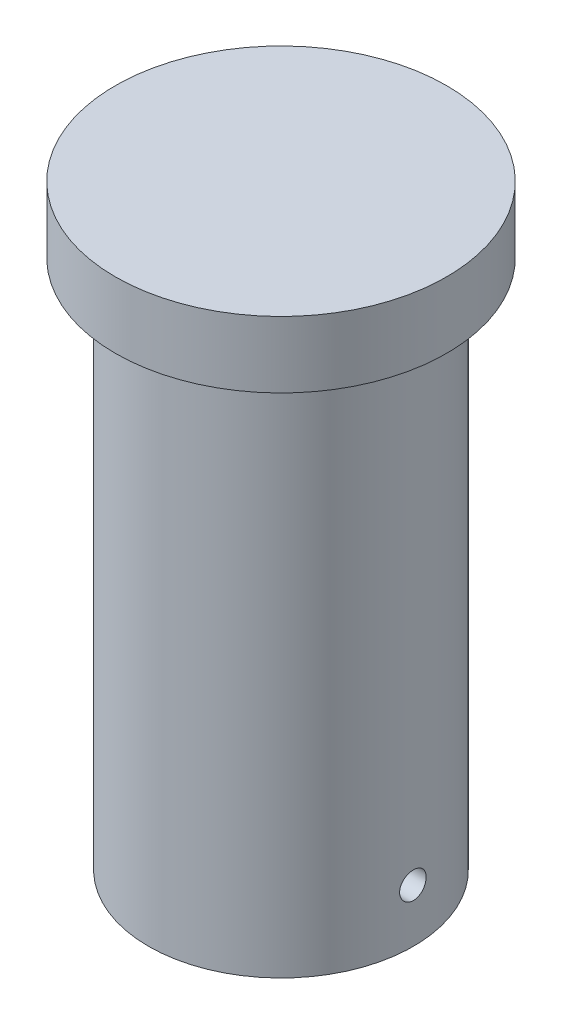
SolidWorks part; units mm, degrees
ref_plane "Front Plane" through (0, 0, 0) normal (0, 0, 1) x (1, 0, 0)
ref_plane "Top Plane" through (0, 0, 0) normal (0, 1, 0) x (1, 0, 0)
ref_plane "Right Plane" through (0, 0, 0) normal (1, 0, 0) x (0, 0, -1)
sketch "Sketch1" plane through (0, 0, 0) normal (0, 1, 0) x (1, 0, 0)
  circle A0 centre (0, 0) radius 5
  dimension "D1" = 10
extrude "Boss-Extrude1" add sketch "Sketch1" along normal blind 20
sketch "Sketch3" plane through (0, 20, 0) normal (0, 1, 0) x (1, 0, 0)
  circle A0 centre (0, 0) radius 6.25
  dimension "D1" = 12.5
extrude "Boss-Extrude3" add sketch "Sketch3" along normal blind 2.5
sketch "Sketch4" plane through (0, 0, 0) normal (1, 0, 0) x (0, 0, -1)
  circle A0 centre (0, 2) radius 0.5
  point P2 (0, 0)
  point P5 (0, 0)
  dimension "D1" = 1
  dimension "D2" = 2
extrude "Cut-Extrude1" cut sketch "Sketch4" against normal through all and the other way through all
